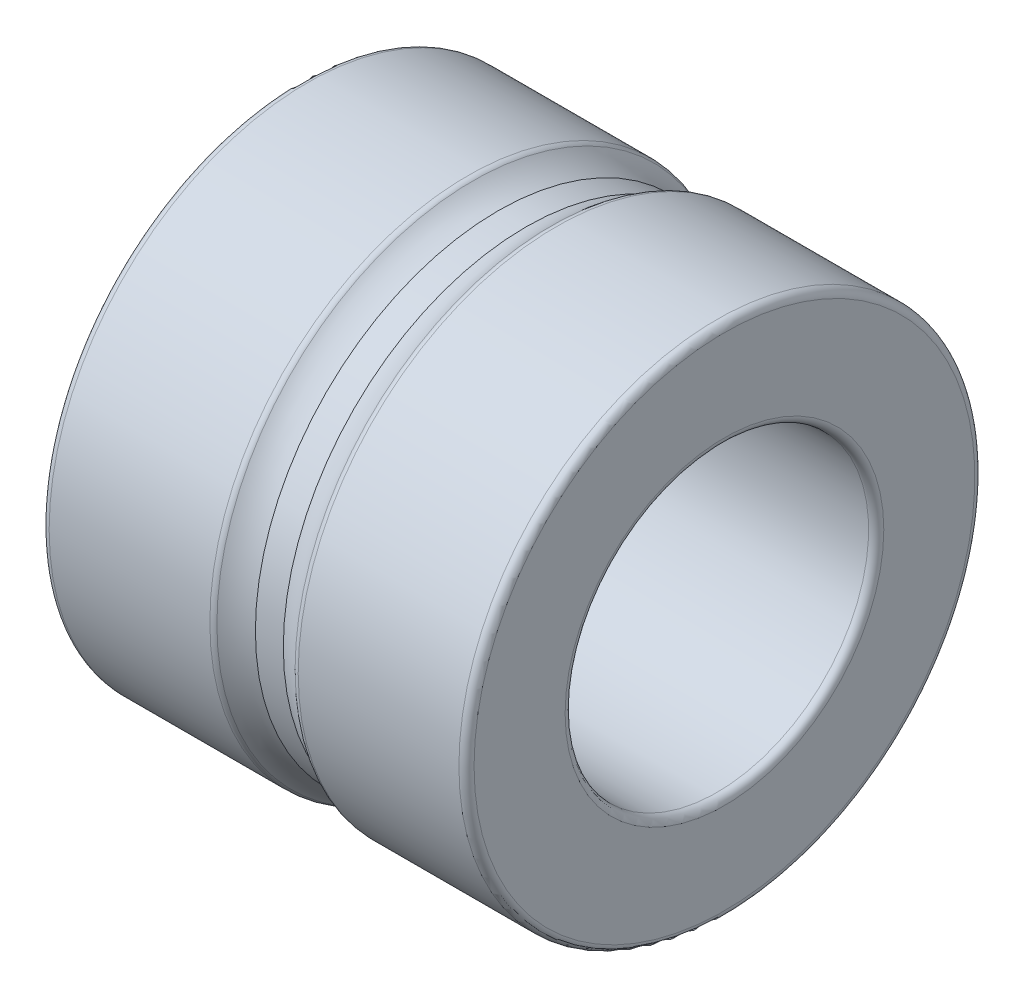
SolidWorks part; units mm, degrees
material "Chrome Stainless Steel"
ref_plane "Front Plane" through (0, 0, 0) normal (0, 0, 1) x (1, 0, 0)
ref_plane "Top Plane" through (0, 0, 0) normal (0, 1, 0) x (1, 0, 0)
ref_plane "Right Plane" through (0, 0, 0) normal (1, 0, 0) x (0, 0, -1)
sketch "Sketch1" plane through (0, 0, 0) normal (0, 0, 1) x (1, 0, 0)
  line L0 (0, 0) -> (6.5174, 0) construction
  line L1 (0, 5) -> (14, 5)
  line L2 (0, 8.5) -> (5.6438, 8.5)
  line L3 (7, 5) -> (7, 7.995) construction
  line L4 (0, 5) -> (0, 8.5)
  line L5 (6.54, 7.995) -> (7.46, 7.995)
  line L6 (14, 5) -> (14, 8.5)
  line L7 (14, 8.5) -> (8.3562, 8.5)
  arc A0 (5.6438, 8.5) -> (6.54, 7.995) centre (7, 9.8591) ccw
  arc A1 (8.3562, 8.5) -> (7.46, 7.995) centre (7, 9.8591) cw
  point P15 (7, 7.995)
  point P19 (7.9426, 8.1864)
  dimension "D1" = 10
  dimension "D4" = 1.92
  dimension "D2" = 17
  dimension "D3" = 14
  dimension "D5" = 0.92
  dimension "D6" = 15.99
revolve "Revolve1" add sketch "Sketch1" angle 360 about L0
fillet "Fillet1" radius 0.25 6 edges at (5.6438, 0, 8.5) (8.3562, 0, 8.5) (0, 0, 5) (14, 0, 5) (0, 0, 8.5) (14, 0, 8.5)
